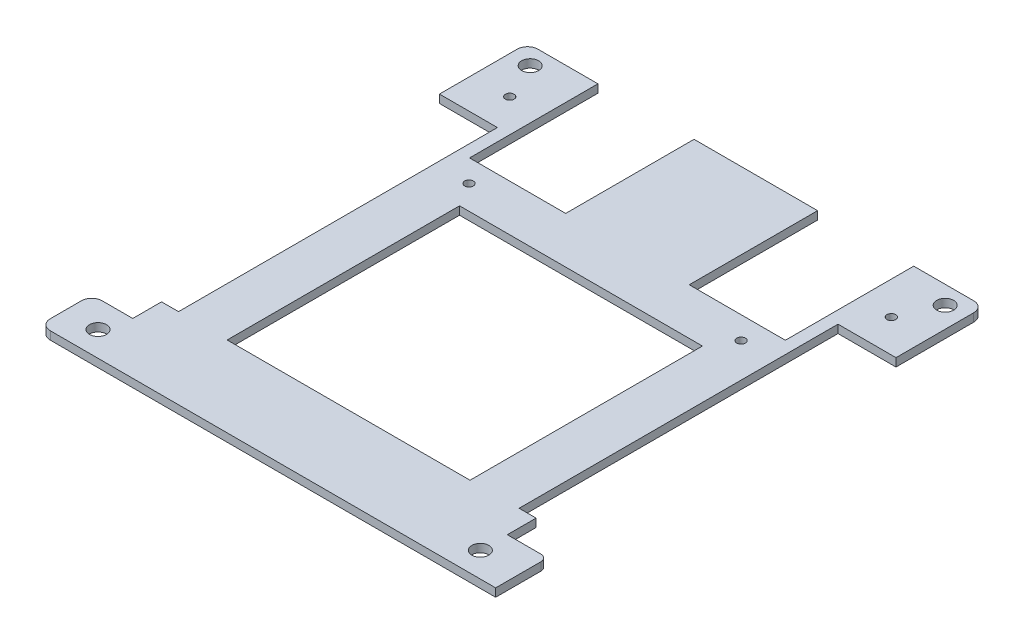
SolidWorks part; units mm, degrees
material "Copper"
ref_plane "Front Plane" through (0, 0, 0) normal (0, 0, 1) x (1, 0, 0)
ref_plane "Top Plane" through (0, 0, 0) normal (0, 1, 0) x (1, 0, 0)
ref_plane "Right Plane" through (0, 0, 0) normal (1, 0, 0) x (0, 0, -1)
sketch "Sketch1" plane through (0, 0, 0) normal (0, 1, 0) x (1, 0, 0)
  line L0 (-44, 45) -> (-44, 30.014)
  line L1 (-44, 30.014) -> (-32.824, 30.014)
  line L2 (-42, 47) -> (42, 47)
  line L3 (44, 45) -> (44, 31.284)
  line L4 (32.824, 30.014) -> (32.824, -31.454)
  line L5 (26.22, 17.9319) -> (-33.6927, 17.9319) construction
  line L6 (32.824, 30.014) -> (44, 30.014)
  line L7 (43.8497, -38.27) -> (43.8497, -47)
  line L8 (42.7059, -47) -> (-42, -47)
  line L9 (-44, -45) -> (-44, -38.977)
  line L10 (-32.824, 30.014) -> (-32.824, -31.454)
  line L11 (32.824, -31.454) -> (36.1, -31.454)
  line L12 (23.409, -31.5) -> (-23.409, -31.5)
  line L13 (-23.409, -31.5) -> (-23.409, 13.2954)
  line L14 (-23.409, 13.2954) -> (-12.909, 13.2954)
  line L15 (-12.909, 13.2954) -> (-12.909, 25.9954)
  line L16 (-12.909, 25.9954) -> (12.909, 25.9954)
  line L17 (12.909, 25.9954) -> (12.909, 13.2954)
  line L18 (12.909, 13.2954) -> (23.409, 13.2954)
  line L19 (23.409, 13.2954) -> (23.409, -31.5)
  line L20 (36.1, -31.454) -> (36.1, -37)
  line L21 (36.1, -37) -> (42.5797, -37)
  line L22 (43.8497, -47) -> (42.7059, -47)
  line L23 (-44, 30.014) -> (52.9697, 30.014) construction
  line L24 (44, 31.284) -> (44, 30.014)
  line L25 (-32.824, -31.454) -> (-36.1, -31.454)
  line L26 (-36.1, -31.454) -> (-36.1, -37)
  line L27 (-36.1, -37) -> (-42, -37)
  circle A0 centre (40, 43.5) radius 1.6383
  circle A1 centre (-40, 43.5) radius 1.6383
  circle A2 centre (-37.6, -42.2) radius 1.6383
  circle A3 centre (36.1, -42.2) radius 1.6383
  arc A4 (42.5797, -37) -> (43.8497, -38.27) centre (42.5797, -38.27) cw
  arc A5 (-42, 47) -> (-44, 45) centre (-42, 45) ccw
  arc A6 (44, 45) -> (42, 47) centre (42, 45) ccw
  circle A8 centre (26.22, 17.9319) radius 0.8382
  circle A9 centre (-26.22, 17.9319) radius 0.8382
  arc A11 (-44, -45) -> (-42, -47) centre (-42, -45) ccw
  arc A12 (-42, -37) -> (-44, -38.977) centre (-42.0115, -38.9885) ccw
  dimension "D24" = 61.468
  dimension "D3" = 80
  dimension "D25" = 1.6764
  dimension "D27" = 1.6764
  dimension "D2" = 6.4
  dimension "D4" = 44.7954
  dimension "D5" = 12.7
  dimension "D6" = 44.7954
  dimension "D7" = 3.5
  dimension "D9" = 4
  dimension "D10" = 3.5
  dimension "D11" = 85.7
  dimension "D12" = 85.7
  dimension "D13" = 21.0046
  dimension "D14" = 11.176
  dimension "D15" = 84
  dimension "D16" = 25.818
  dimension "D17" = 12.7
  dimension "D18" = 46.818
  dimension "D19" = 10.5
  dimension "D20" = 10.5
  dimension "D21" = 73.7
  dimension "D23" = 13.716
  dimension "D26" = 6.604
  dimension "D28" = 6.604
  dimension "D29" = 11.176
  dimension "D30" = 61.468
  dimension "D31" = 3.276
  dimension "D32" = 3.276
extrude "Boss-Extrude1" add sketch "Sketch1" along normal blind 1.575
sketch "Sketch2" plane through (0, 1.575, 0) normal (0, 1, 0) x (1, 0, 0)
  line L0 (-12.909, 19.06) -> (-30.435, 19.06)
  line L1 (42, 47) -> (-42, 47) construction
  line L2 (-12.909, 25.9954) -> (12.909, 25.9954) construction
  line L3 (-30.435, 47) -> (30.435, 47)
  line L4 (12.909, 13.2954) -> (12.909, 25.9954) construction
  line L5 (12.909, 19.06) -> (30.435, 19.06)
  line L6 (30.435, 19.06) -> (30.435, 47)
  line L7 (0, 47) -> (0, -47) construction
  line L8 (-42, -47) -> (43.8497, -47) construction
  line L9 (-12.909, 25.9954) -> (-12.909, 19.06)
  line L10 (-30.435, 19.06) -> (-30.435, 47)
  line L11 (12.909, 25.9954) -> (12.909, 19.06)
  line L13 (-12.909, 25.9954) -> (12.909, 25.9954)
  dimension "D1" = 27.94
  dimension "D2" = 17.526
extrude "Cut-Extrude1" cut sketch "Sketch2" against normal blind 2.54
sketch "Sketch15" plane through (0, 1.575, 0) normal (0, 1, 0) x (1, 0, 0)
  line L0 (-30.435, 47) -> (-30.435, 19.06) construction
  line L4 (42, 47) -> (30.435, 47) construction
  line L5 (30.435, 19.06) -> (30.435, 47) construction
  circle A0 centre (-36.785, 36.35) radius 0.8382
  circle A1 centre (36.785, 36.332) radius 0.8382
  dimension "D1" = 1.6764
  dimension "D3" = 1.6764
  dimension "D4" = 10.668
  dimension "D2" = 6.35
  dimension "D5" = 6.35
extrude "Cut-Extrude5" cut sketch "Sketch15" against normal blind 1.575
sketch "Sketch16" plane through (0, 1.575, 0) normal (0, 1, 0) x (1, 0, 0)
  line L1 (12.909, 19.06) -> (12.909, 13.2954)
  line L2 (12.909, 13.2954) -> (-12.909, 13.2954)
  line L3 (-11.909, 47) -> (-11.909, 22.2554)
  line L4 (-30.435, 22.2554) -> (-11.909, 22.2554)
  line L5 (11.909, 22.2554) -> (11.909, 47)
  line L6 (11.909, 47) -> (-11.909, 47)
  line L7 (-30.435, 47) -> (-30.435, 19.06) construction
  line L9 (-12.909, 19.06) -> (-12.909, 13.2954)
  line L10 (-30.435, 47) -> (-42, 47) construction
  line L11 (11.909, 22.2554) -> (30.435, 22.2554)
  line L12 (30.435, 19.06) -> (30.435, 47) construction
  line L13 (30.435, 22.2554) -> (30.435, 19.06)
  line L14 (30.435, 19.06) -> (12.909, 19.06)
  line L15 (-30.435, 22.2554) -> (-30.435, 19.06)
  line L16 (-30.435, 19.06) -> (-12.909, 19.06)
  dimension "D1" = 24.7446
extrude "Boss-Extrude2" add sketch "Sketch16" against normal blind 1.575
